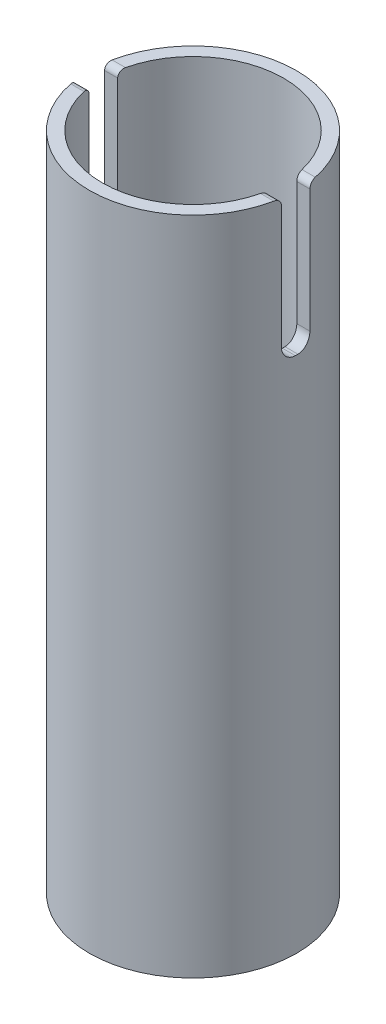
SolidWorks part; units mm, degrees
ref_plane "前视基准面" through (0, 0, 0) normal (0, 0, 1) x (1, 0, 0)
ref_plane "上视基准面" through (0, 0, 0) normal (0, 1, 0) x (1, 0, 0)
ref_plane "右视基准面" through (0, 0, 0) normal (1, 0, 0) x (0, 0, -1)
sketch "草图1" plane through (0, 0, 0) normal (0, 1, 0) x (1, 0, 0)
  circle A0 centre (0, 0) radius 8
  dimension "D1" = 16
extrude "凸台-拉伸1" add sketch "草图1" along normal blind 51
sketch "草图2" plane through (0, 51, 0) normal (0, 1, 0) x (1, 0, 0)
  circle A0 centre (0, 0) radius 7
  dimension "D1" = 14
extrude "切除-拉伸1" cut sketch "草图2" against normal blind 38
sketch "草图3" plane through (0, 0, 0) normal (1, 0, 0) x (0, 0, -1)
  line L0 (8, 51) -> (-8, 51) construction
  line L1 (-1.1, 62) -> (1.1, 62)
  line L2 (-1.1, 62) -> (-1.1, 40)
  line L3 (-1.1, 40) -> (1.1, 40)
  line L4 (1.1, 62) -> (1.1, 40)
  line L5 (-1.1, 62) -> (1.1, 40) construction
  line L6 (-1.1, 40) -> (1.1, 62) construction
  point P0 (0, 51)
  dimension "D1" = 22
  dimension "D2" = 2.2
extrude "切除-拉伸2" cut sketch "草图3" against normal through all both and the other way through all
fillet "圆角1" radius 0.5 4 edges at (7.4185, 51, 1.1) (-7.4185, 51, 1.1) (-7.4185, 51, -1.1) (7.4185, 51, -1.1)
fillet "圆角2" radius 1 4 edges at (7.4185, 40, 1.1) (-7.4185, 40, 1.1) (-7.4185, 40, -1.1) (7.4185, 40, -1.1)
sketch "草图4" plane through (0, 0, 0) normal (0, -1, 0) x (-1, 0, 0)
  circle A0 centre (0, 0) radius 3
  dimension "D1" = 6
extrude "切除-拉伸3" cut sketch "草图4" against normal through all
sketch "草图5" plane through (0, 0, 0) normal (0, -1, 0) x (1, 0, 0)
  circle A0 centre (0, 5.5) radius 1.5
  arc A2 (6.8147, 1.6) -> (-6.8147, 1.6) centre (0, 0) ccw construction
  dimension "D1" = 3
extrude "切除-拉伸8" cut sketch "草图5" against normal blind 38
